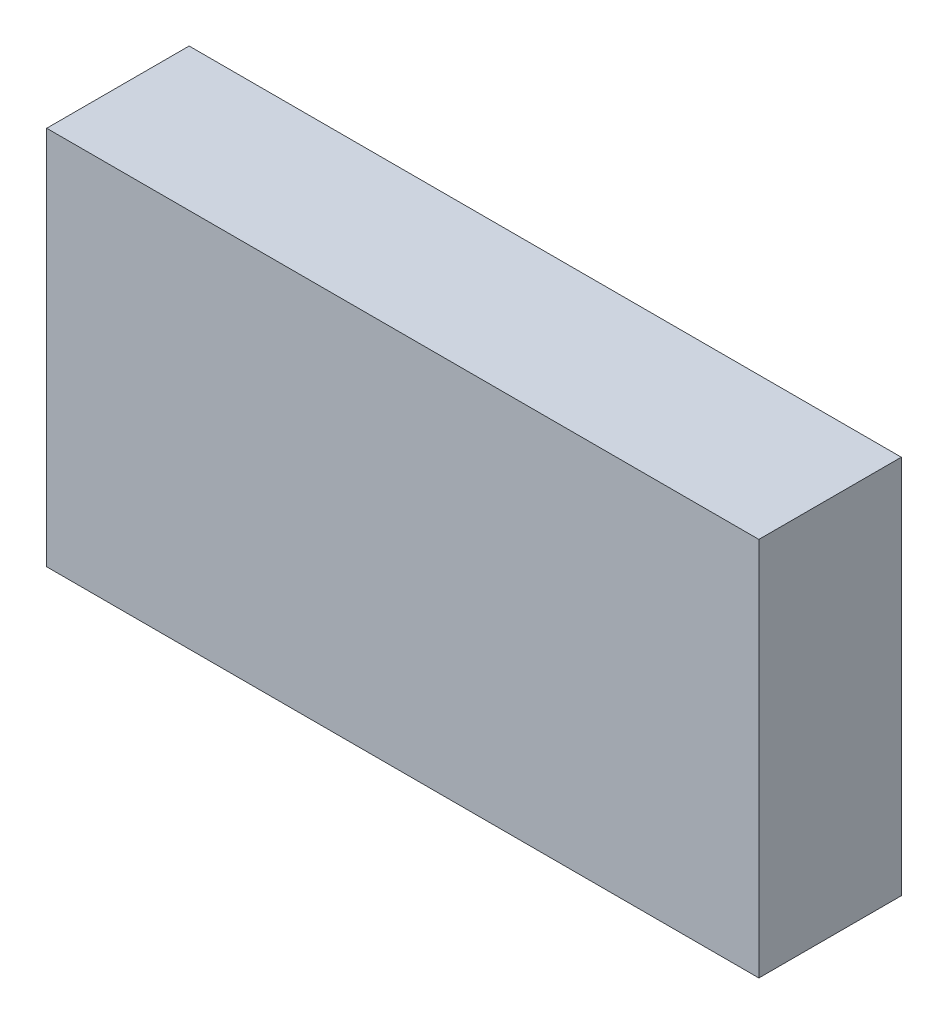
SolidWorks part; units mm, degrees
ref_plane "Front Plane" through (0, 0, 0) normal (0, 0, 1) x (1, 0, 0)
ref_plane "Top Plane" through (0, 0, 0) normal (0, 1, 0) x (1, 0, 0)
ref_plane "Right Plane" through (0, 0, 0) normal (1, 0, 0) x (0, 0, -1)
other "Configuration Table"
sketch "Sketch1" plane through (0, 0, 0) normal (0, 0, 1) x (1, 0, 0)
  line L1 (596, 74) -> (611, 74)
  line L2 (596, 74) -> (596, 82)
  line L3 (596, 82) -> (611, 82)
  line L4 (611, 74) -> (611, 82)
extrude "CEK_donmus_miknatis_15x8x3_1" add sketch "Sketch1" against normal blind 3 separate body
